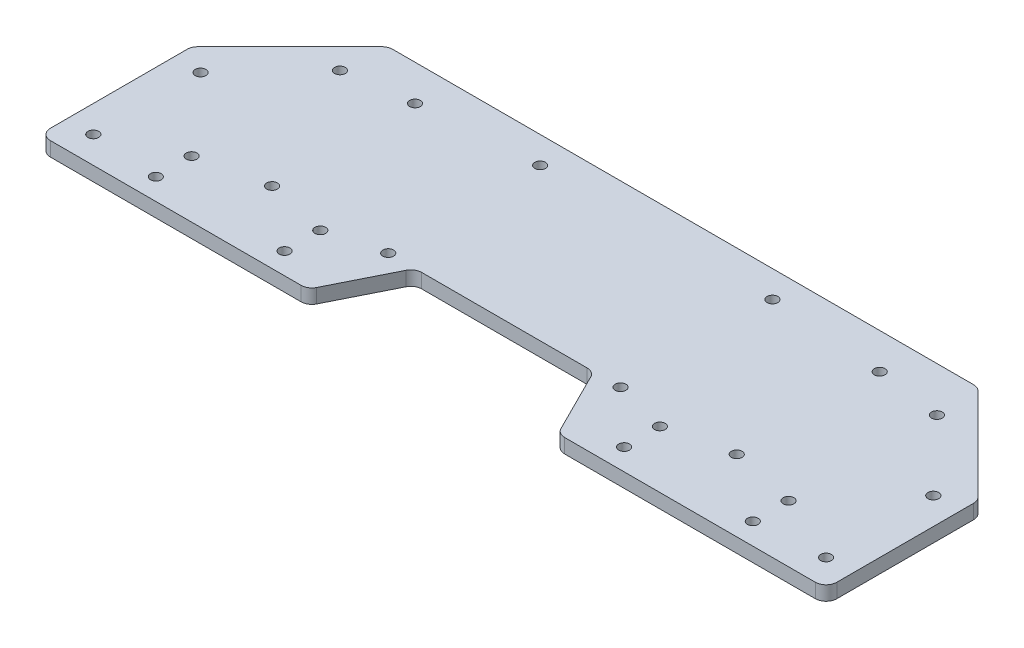
SolidWorks part; units mm, degrees
ref_plane "前视基准面" through (0, 0, 0) normal (0, 0, 1) x (1, 0, 0)
ref_plane "上视基准面" through (0, 0, 0) normal (0, 1, 0) x (1, 0, 0)
ref_plane "右视基准面" through (0, 0, 0) normal (1, 0, 0) x (0, 0, -1)
sketch "草图1" plane through (0, 0, 0) normal (0, 1, 0) x (1, 0, 0)
  line L1 (-137.5, -35) -> (-67.5, -35)
  line L2 (-137.5, -35) -> (-137.5, 15)
  line L3 (-117.5, 35) -> (72.5, 35)
  line L4 (92.5, -35) -> (92.5, 15)
  line L5 (22.5, -35) -> (92.5, -35)
  line L6 (-137.5, 15) -> (-117.5, 35)
  line L7 (-22.5, 61.4781) -> (-22.5, -135.1347) construction
  line L8 (92.5, 15) -> (72.5, 35)
  line L9 (-47.5, -15) -> (2.5, -15)
  line L10 (-67.5, -35) -> (-57.5, -35)
  line L11 (-57.5, -35) -> (-47.5, -15)
  line L12 (22.5, -35) -> (12.5, -35)
  line L14 (12.5, -35) -> (2.5, -15)
  point P0 (0, 0)
  point P6 (0, -35)
  dimension "D1" = 230
  dimension "D2" = 10
  dimension "D3" = 50
  dimension "D4" = 20
  dimension "D5" = 70
  dimension "D6" = 70
  dimension "D7" = 135
  dimension "D8" = 20
  dimension "D9" = 10
extrude "凸台-拉伸1" add sketch "草图1" along normal blind 4
sketch "草图2" plane through (0, 4, 0) normal (0, 1, 0) x (1, 0, 0)
  line L0 (-137.5, -35) -> (-57.5, -35) construction
  line L1 (-47.5, -15) -> (2.5, -15) construction
  line L2 (-22.5, 54.05) -> (-22.5, -68.4645) construction
  circle A0 centre (-87.5, -15) radius 1.5
  circle A1 centre (-87.5, 25) radius 1.5
  circle A2 centre (42.5, 25) radius 1.5
  circle A3 centre (42.5, -15) radius 1.5
  point P8 (-22.5, -15)
  dimension "D1" = 40
  dimension "D2" = 20
  dimension "D3" = 65
extrude "切除-拉伸1" cut sketch "草图2" against normal blind 4
sketch "草图3" plane through (0, 4, 0) normal (0, 1, 0) x (1, 0, 0)
  line L1 (-137.5, -35) -> (-127.5, -35)
  line L2 (-137.5, -35) -> (-137.5, 34.6789)
  line L3 (-137.5, 34.6789) -> (-127.5, 34.6789)
  line L4 (-127.5, -35) -> (-127.5, 34.6789)
  line L5 (92.5, -35) -> (82.5, -35)
  line L6 (92.5, -35) -> (92.5, 58.0477)
  line L7 (92.5, 58.0477) -> (82.5, 58.0477)
  line L8 (82.5, -35) -> (82.5, 58.0477)
  dimension "D1" = 10
  dimension "D2" = 10
extrude "切除-拉伸2" cut sketch "草图3" against normal blind 4
sketch "草图4" plane through (0, 4, 0) normal (0, 1, 0) x (1, 0, 0)
  line L0 (-127.5, 12.5) -> (-92.1971, 47.8029)
  line L1 (-127.5, -35) -> (-127.5, 25) construction
  line L2 (-92.1971, 47.8029) -> (-150.179, 47.8029)
  line L3 (-150.179, 47.8029) -> (-127.5, 12.5)
  line L4 (82.5, 12.5) -> (37.0053, 57.9947)
  line L5 (82.5, 25) -> (82.5, -35) construction
  line L6 (37.0053, 57.9947) -> (96.5441, 56.2052)
  line L7 (96.5441, 56.2052) -> (82.5, 12.5)
  line L8 (-127.5, -35) -> (-57.5, -35) construction
  line L9 (12.5, -35) -> (82.5, -35) construction
  dimension "D1" = 47.5
  dimension "D2" = 47.5
extrude "切除-拉伸3" cut sketch "草图4" against normal blind 4
sketch "草图5" plane through (0, 4, 0) normal (0, 1, 0) x (1, 0, 0)
  line L0 (-127.5, 12.5) -> (-132.5, 7.5)
  line L1 (-132.5, 7.5) -> (-132.5, -35)
  line L2 (-132.5, -35) -> (-127.5, -35)
  line L3 (-127.5, -35) -> (-127.5, 12.5)
  line L4 (-22.5, 45.9563) -> (-22.5, -39.7367) construction
  line L5 (82.5, -35) -> (82.5, 12.5)
  line L6 (87.5, -35) -> (82.5, -35)
  line L7 (87.5, 7.5) -> (87.5, -35)
  line L8 (82.5, 12.5) -> (87.5, 7.5)
  line L9 (-127.5, 12.5) -> (-105, 35) construction
  dimension "D1" = 5
extrude "凸台-拉伸2" add sketch "草图5" against normal up to surface (4 mm away) up to face at (-22.5, 0, 7.5)
sketch "草图6" plane through (0, 4, 0) normal (0, 1, 0) x (1, 0, 0)
  line L0 (12.5, -35) -> (87.5, -35) construction
  line L1 (-22.5, 44.5061) -> (-22.5, -48.9521) construction
  circle A0 centre (61, -29) radius 1.5
  circle A1 centre (42.5, -15) radius 1.5 construction
  circle A2 centre (61, -19) radius 1.5
  circle A3 centre (25, -19) radius 1.5
  circle A4 centre (25, -29) radius 1.5
  circle A5 centre (-70, -29) radius 1.5
  circle A6 centre (-70, -19) radius 1.5
  circle A7 centre (-106, -19) radius 1.5
  circle A8 centre (-106, -29) radius 1.5
  dimension "D1" = 18.5
  dimension "D2" = 6
  dimension "D3" = 10
  dimension "D4" = 2
extrude "切除-拉伸4" cut sketch "草图6" against normal blind 10
fillet "圆角1" radius 3 10 edges at (60, 2, -35) (-105, 2, -35) (-132.5, 2, -7.5) (-132.5, 2, 35) (-57.5, 2, 35) (-47.5, 2, 15) (2.5, 2, 15) (12.5, 2, 35) (87.5, 2, -7.5) (87.5, 2, 35)
sketch "草图7" plane through (0, 4, 0) normal (0, 1, 0) x (1, 0, 0)
  line L0 (14.3541, -35) -> (84.5, -35) construction
  line L1 (87.5, -32) -> (87.5, 6.2574) construction
  line L2 (-22.5, 50.3145) -> (-22.5, -50.3433) construction
  line L3 (58.7574, 35) -> (-103.7574, 35) construction
  line L4 (-45.6459, -15) -> (0.6459, -15) construction
  circle A0 centre (80, -27.5) radius 1.5032
  circle A1 centre (80, 2.5) radius 1.5032
  circle A2 centre (-125, 2.5) radius 1.5032
  circle A3 centre (-125, -27.5) radius 1.5032
  circle A4 centre (10, -15) radius 1.5
  circle A5 centre (10, 27.5) radius 1.5
  circle A6 centre (-55, 27.5) radius 1.5
  circle A7 centre (-55, -15) radius 1.5
  point P26 (-22.5, -15)
  dimension "D1" = 7.5
  dimension "D2" = 7.5
  dimension "D4" = 32.5
  dimension "D5" = 7.5
  dimension "D6" = 0
  dimension "D7" = 0
  dimension "D3" = 2
extrude "切除-拉伸5" cut sketch "草图7" against normal blind 10
sketch "草图8" plane through (0, 4, 0) normal (0, 1, 0) x (1, 0, 0)
  line L0 (-22.5, 46.7435) -> (-22.5, -35.4694) construction
  circle A0 centre (61, 22.5) radius 1.5
  circle A1 centre (61, -19) radius 1.5 construction
  circle A2 centre (-106, 22.5) radius 1.5
  dimension "D1" = 41.5
extrude "切除-拉伸6" cut sketch "草图8" against normal blind 10
